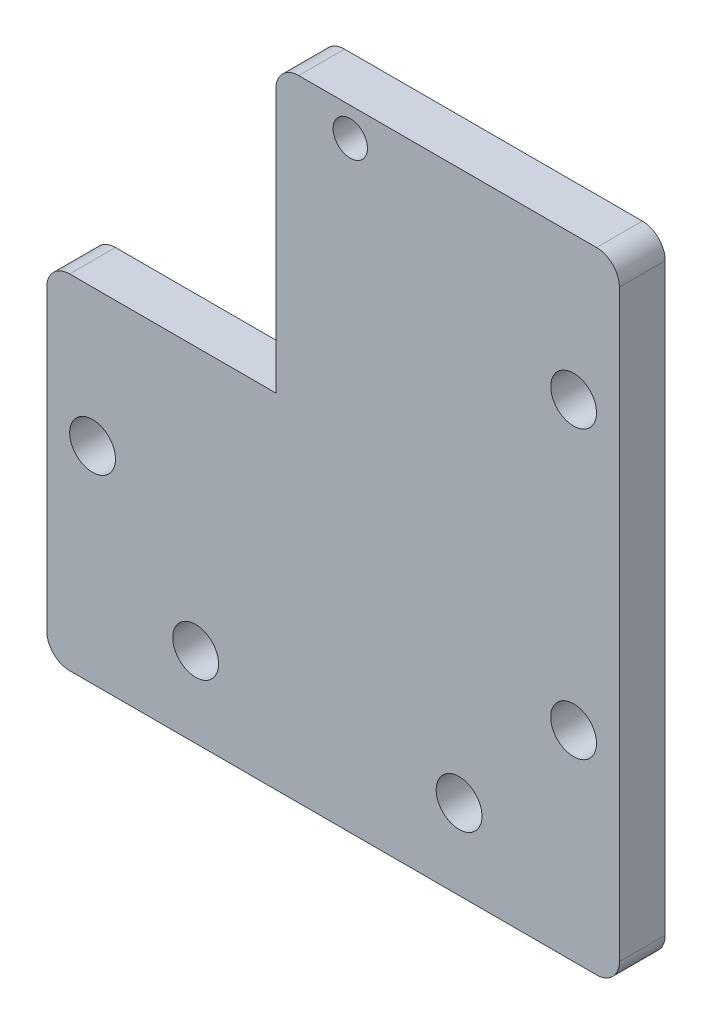
SolidWorks part; units mm, degrees
ref_plane "Front Plane" through (0, 0, 0) normal (0, 0, 1) x (1, 0, 0)
ref_plane "Top Plane" through (0, 0, 0) normal (0, 1, 0) x (1, 0, 0)
ref_plane "Right Plane" through (0, 0, 0) normal (1, 0, 0) x (0, 0, -1)
sketch "Sketch1" plane through (0, 0, 0) normal (0, 0, 1) x (1, 0, 0)
  line L1 (-30, 55) -> (0, 55)
  line L2 (-50, 30) -> (-50, 0)
  line L3 (-50, 0) -> (0, 0)
  line L4 (0, 55) -> (0, 0)
  line L7 (-50, 30) -> (-30, 30)
  line L8 (-30, 55) -> (-30, 30)
  dimension "D1" = 50
  dimension "D2" = 55
  dimension "D3" = 20
  dimension "D4" = 25
extrude "Boss-Extrude1" add sketch "Sketch1" along normal blind 4
fillet "Fillet1" radius 2 5 edges at (-50, 0, 2) (0, 0, 2) (0, 55, 2) (-30, 55, 2) (-50, 30, 2)
sketch "Sketch3" plane through (0, 0, 4) normal (0, 0, 1) x (1, 0, 0)
  circle A0 centre (-23.5, 52.5) radius 1.5 construction
  circle A1 centre (-46, 18) radius 2 construction
  circle A2 centre (-37, 7) radius 2 construction
  circle A3 centre (-14, 7) radius 2 construction
  circle A4 centre (-4, 17.5) radius 2 construction
  circle A5 centre (-4, 42.5) radius 2 construction
  circle A6 centre (-23.5, 52.5) radius 1.5
  circle A7 centre (-46, 18) radius 2
  circle A8 centre (-37, 7) radius 2
  circle A9 centre (-14, 7) radius 2
  circle A10 centre (-4, 17.5) radius 2
  circle A11 centre (-4, 42.5) radius 2
extrude "Cut-Extrude1" cut sketch "Sketch3" against normal blind 10
